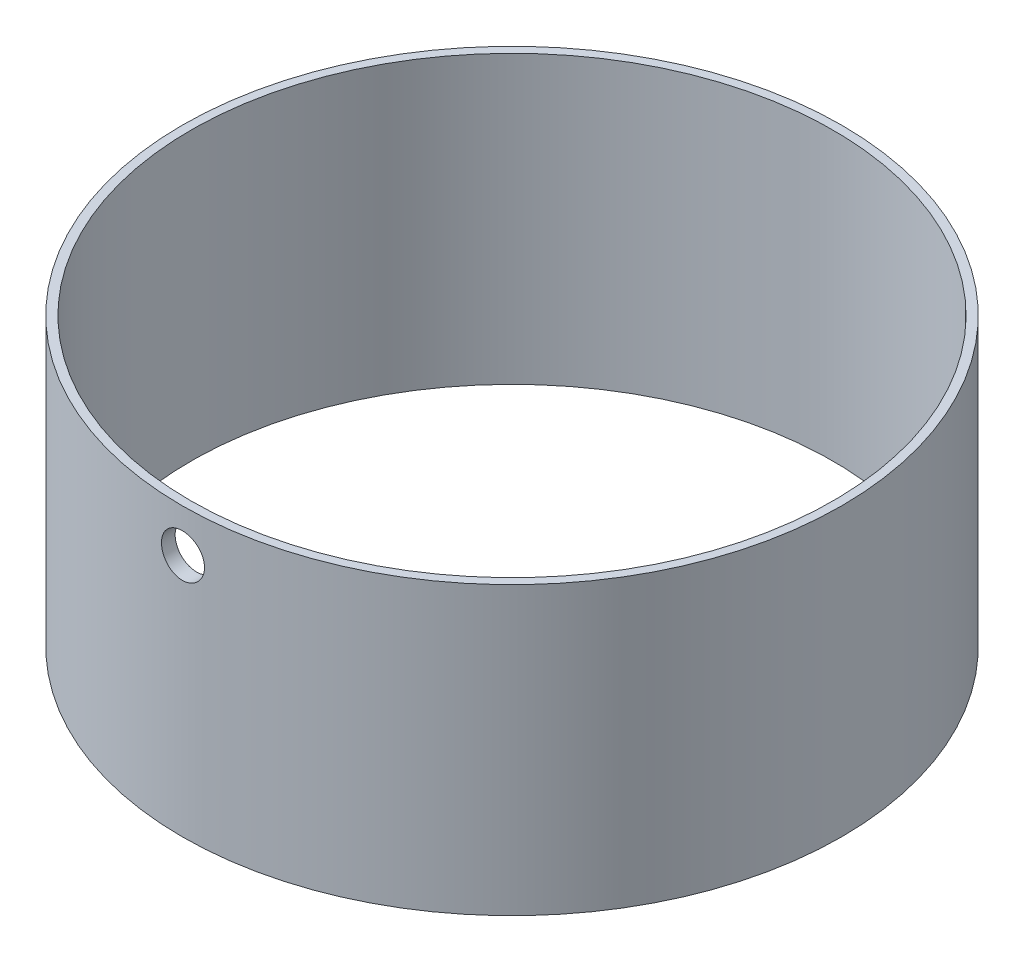
SolidWorks part; units mm, degrees
ref_plane "Front Plane" through (0, 0, 0) normal (0, 0, 1) x (1, 0, 0)
ref_plane "Top Plane" through (0, 0, 0) normal (0, 1, 0) x (1, 0, 0)
ref_plane "Right Plane" through (0, 0, 0) normal (1, 0, 0) x (0, 0, -1)
sketch "Sketch2" plane through (0, 0, 0) normal (0, 1, 0) x (1, 0, 0)
  circle A0 centre (0, 0) radius 115
  dimension "D1" = 230
extrude "Boss-Extrude3" add sketch "Sketch2" along normal blind 100
sketch "Sketch3" plane through (0, 100, 0) normal (0, 1, 0) x (1, 0, 0)
  circle A0 centre (0, 0) radius 112
  circle A1 centre (0, 0) radius 115 construction
  dimension "D1" = 3
extrude "Cut-Extrude4" cut sketch "Sketch3" against normal through all
ref_plane "Plane3" through (0, 0, 110) normal (0, 0, 1) x (1, 0, 0)
sketch "Sketch4" plane through (0, 0, 110) normal (0, 0, 1) x (1, 0, 0)
  line L0 (115, 100) -> (-115, 100) construction
  circle A0 centre (0, 85) radius 7.5
  dimension "D1" = 15
  dimension "D2" = 15
extrude "Cut-Extrude5" cut sketch "Sketch4" along normal through all contours A0
sketch "Sketch6" plane through (0, 0, 110) normal (0, 0, 1) x (1, 0, 0)
  line L0 (112, 100) -> (-112, 100) construction
  line L1 (12.1886, 95) -> (-11.8114, 95)
  line L2 (12.1886, 95) -> (12.1886, 69)
  line L3 (12.1886, 69) -> (-11.8114, 69)
  line L4 (-11.8114, 95) -> (-11.8114, 69)
  line L5 (12.1886, 95) -> (-11.8114, 69) construction
  line L6 (12.1886, 69) -> (-11.8114, 95) construction
  point P0 (0.1886, 82)
  dimension "D1" = 24
  dimension "D2" = 26
  dimension "D3" = 5
extrude "Boss-Extrude4" add sketch "Sketch6" along normal blind 2
sketch "Sketch7" plane through (0, 0, 110) normal (0, 0, -1) x (-1, 0, 0)
  circle A0 centre (0, 85) radius 7.5
extrude "Cut-Extrude6" cut sketch "Sketch7" against normal through all
